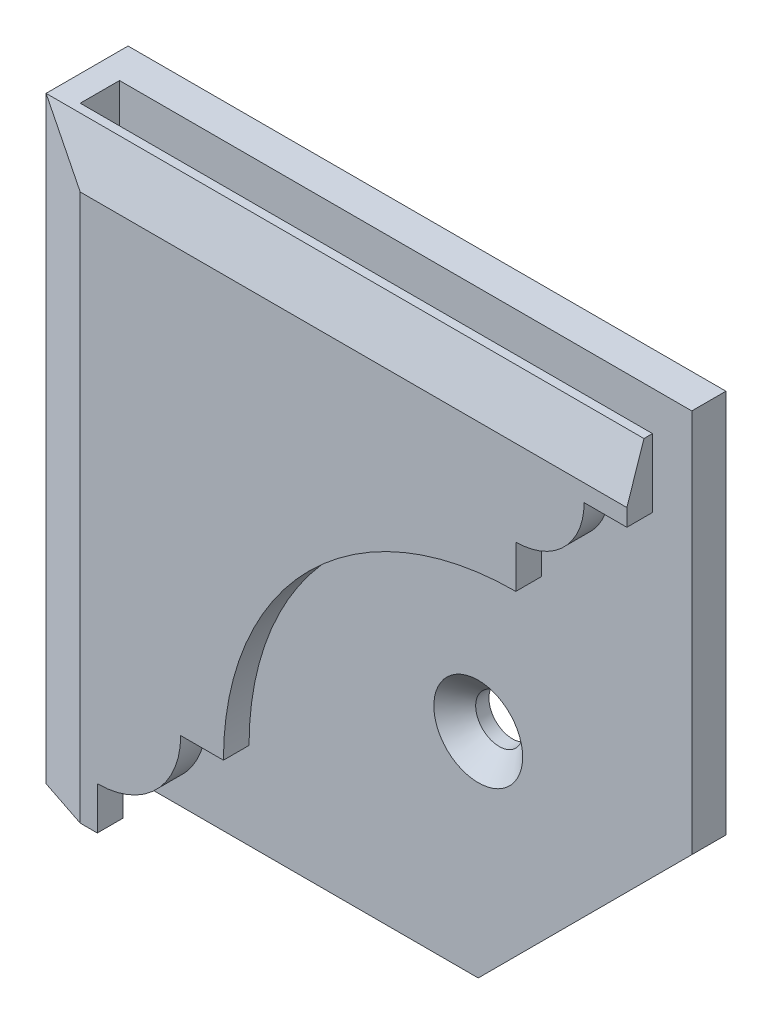
SolidWorks part; units mm, degrees
ref_plane "Plan de face" through (0, 0, 0) normal (0, 0, 1) x (1, 0, 0)
ref_plane "Plan de dessus" through (0, 0, 0) normal (0, 1, 0) x (1, 0, 0)
ref_plane "Plan de droite" through (0, 0, 0) normal (1, 0, 0) x (0, 0, -1)
sketch "Esquisse1" plane through (0, 0, 0) normal (0, 0, 1) x (1, 0, 0)
  line L1 (-35, -35) -> (35, -35)
  line L2 (-35, -35) -> (-35, 35)
  line L3 (-35, 35) -> (35, 35)
  line L4 (35, -35) -> (35, 35)
  line L5 (-35, -35) -> (35, 35) construction
  line L6 (-35, 35) -> (35, -35) construction
  point P0 (0, 0)
  dimension "D1" = 70
extrude "Boss.-Extru.1" add sketch "Esquisse1" along normal blind 4
sketch "Esquisse2" plane through (0, 0, 4) normal (0, 0, 1) x (1, 0, 0)
  line L0 (-35, 35) -> (-35, -35) construction
  line L1 (35, 35) -> (-35, 35) construction
  line L2 (-35, 35) -> (-35, -35)
  line L3 (35, 35) -> (-35, 35)
  line L4 (-35, -35) -> (-32, -35)
  line L6 (-35, -35) -> (35, -35) construction
  line L7 (-32, -35) -> (-32, 32)
  line L8 (-32, 32) -> (35, 32)
  line L9 (35, -35) -> (35, 35) construction
  line L11 (35, 32) -> (35, 35)
  dimension "D1" = 3
extrude "Boss.-Extru.2" add sketch "Esquisse2" along normal blind 4.6
sketch "Esquisse3" plane through (0, 0, 8.6) normal (0, 0, 1) x (1, 0, 0)
  line L0 (35, 35) -> (-35, 35) construction
  line L1 (-35, 35) -> (-35, -35) construction
  line L2 (35, 35) -> (-35, 35)
  line L3 (-35, 35) -> (-35, -35)
  line L4 (35, 35) -> (35, 27)
  line L5 (35, -35) -> (35, 32) construction
  line L6 (35, 27) -> (30, 27)
  line L7 (22, 19) -> (22, 14)
  line L8 (-12.235, -20.235) -> (-17.235, -20.235)
  line L9 (-27, -30) -> (-27, -35)
  line L10 (-32, -35) -> (35, -35) construction
  line L11 (-27, -35) -> (-35, -35)
  arc A0 (30, 27) -> (22, 19) centre (22, 27) cw
  arc A1 (22, 14) -> (-12.235, -20.235) centre (22, -20.235) ccw
  arc A2 (-17.235, -20.235) -> (-27, -30) centre (-27, -20.235) cw
  dimension "D3" = 8
  dimension "D1" = 8
  dimension "D2" = 5
extrude "Boss.-Extru.3" add sketch "Esquisse3" along normal blind 3
chamfer "Chanfrein1" distance 2 distance2 6 2 edges at (-35, 0, 11.6) (0, 35, 11.6)
chamfer "Chanfrein2" distance 25 angle 45 1 edges at (35, -35, 2)
hole_wizard "Fraisage pour vis à tête fraisée M51" positions "Esquisse5" profile "Esquisse4" countersink size "M5" standard "Ansi Metric" end condition up to next
sketch "Esquisse5" plane through (0, 0, 4) normal (0, 0, 1) x (1, 0, 0)
  line L0 (35, -10) -> (35, 32) construction
  line L1 (-32, -35) -> (10, -35) construction
  point P0 (10, -10)
  dimension "D1" = 25
  dimension "D2" = 25
sketch "Esquisse4" plane through (10, -10, 4) normal (1, 0, 0) x (0, -1, 0)
  line L0 (0, 0) -> (0, 4)
  line L1 (0, 4) -> (2.75, 4)
  line L2 (2.75, 4) -> (2.75, 2.45)
  line L3 (2.75, 2.45) -> (5.2, 0)
  line L5 (5.2, 0) -> (0, 0)
  line L6 (-2.75, 2.45) -> (-5.2, 0) construction
  line L11 (0, -6.35) -> (0, 107.95) construction
  dimension "Diamètre du perçage jusqu'au prochain" = 5.5
  dimension "Profondeur du perçage jusqu'au prochain" = 4
  dimension "Diamètre du fraisage entrant" = 10.4
  dimension "Angle du fraisage entrant" = 90
sketch "Esquisse6" plane through (0, 32, 0) normal (0, -1, 0) x (1, 0, 0)
  line L4 (-32, 4) -> (35, 4)
  line L5 (35, 4) -> (35, 8.6)
  line L6 (35, 8.6) -> (-32, 8.6)
  line L7 (-32, 8.6) -> (-32, 4)
  line L8 (-32, 4) -> (35, 4)
  line L9 (35, 4) -> (35, 8.6)
  line L10 (35, 8.6) -> (-32, 8.6)
  line L11 (-32, 8.6) -> (-32, 4)
  dimension "D1" = 0
extrude "Enlèv. mat.-Extru.1" cut sketch "Esquisse6" against normal up to next
